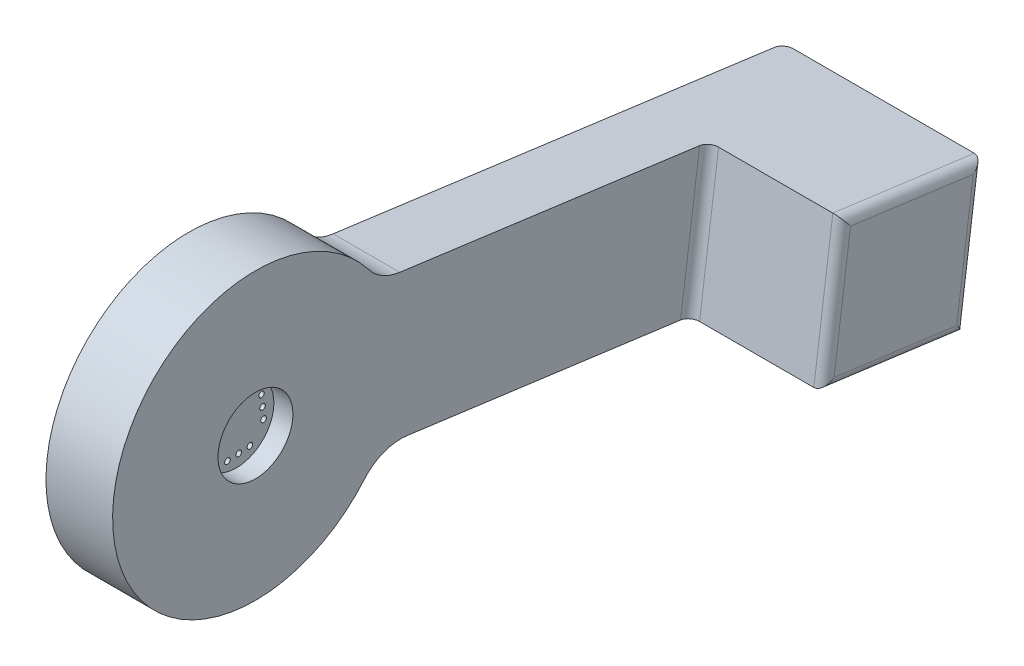
SolidWorks part; units mm, degrees
ref_plane "Front Plane" [suppressed] through (0, 0, 0) normal (0, 0, 1) x (1, 0, 0)
ref_plane "Top Plane" [suppressed] through (0, 0, 0) normal (0, 1, 0) x (1, 0, 0)
ref_plane "Right Plane" through (0, 0, 0) normal (1, 0, 0) x (0, 0, -1)
sketch "Sketch1" plane through (0, 0, 0) normal (1, 0, 0) x (0, 0, -1)
  line L4 (32.8966, -19.2204) -> (153.708, -35.4166)
  line L5 (153.708, -35.4166) -> (158.7705, 2.3455)
  line L6 (158.7705, 2.3455) -> (32.8966, 19.2204)
  arc A2 (32.8966, 19.2204) -> (32.8966, -19.2204) centre (0, 0) ccw
  dimension "D2" = 127
  dimension "D1" = 38.1
  dimension "D3" = 38.1
extrude "Boss-Extrude1" add sketch "Sketch1" along normal blind 17.78
sketch "Sketch2" plane through (17.78, 0, 0) normal (1, 0, 0) x (0, 0, -1)
  circle A0 centre (0, 0) radius 10
extrude "Cut-Extrude2" cut sketch "Sketch2" against normal blind 5.08
sketch "Sketch8" plane through (12.7, 0, 0) normal (1, 0, 0) x (0, 0, -1)
  circle A12 centre (-7.2367, 2.3729) radius 0.75
  circle A13 centre (-6.9729, -0.6155) radius 0.75
  circle A14 centre (-6.7091, -3.6039) radius 0.75
  circle A15 centre (-2.3729, -7.2367) radius 0.75
  circle A16 centre (0.6155, -6.9729) radius 0.75
  circle A17 centre (3.6039, -6.7091) radius 0.75
  circle A18 centre (7.2367, -2.3729) radius 0.75
  circle A19 centre (6.9729, 0.6155) radius 0.75
  circle A20 centre (6.7091, 3.6039) radius 0.7248
  circle A21 centre (2.3729, 7.2367) radius 0.75
  circle A22 centre (-0.6155, 6.9729) radius 0.75
  circle A23 centre (-3.6039, 6.7091) radius 0.7425
extrude "Cut-Extrude7" cut sketch "Sketch8" against normal blind 5.08
sketch "Sketch4" plane through (17.78, 0, 0) normal (1, 0, 0) x (0, 0, -1)
  line L0 (158.7705, 2.3455) -> (153.708, -35.4166)
  line L1 (158.7705, 2.3455) -> (121.0083, 7.408)
  line L2 (153.708, -35.4166) -> (115.9458, -30.3542)
  line L3 (121.0083, 7.408) -> (115.9458, -30.3542)
  line L4 (158.7705, 2.3455) -> (115.9458, -30.3542) construction
  line L5 (121.0083, 7.408) -> (153.708, -35.4166) construction
  line L6 (156.2392, -16.5355) -> (137.3582, -14.0043) construction
  dimension "D1" = 38.1
  dimension "D2" = 38.1
extrude "Boss-Extrude2" add sketch "Sketch4" along normal blind 35.56
sketch "Sketch7" plane through (0, -20.8679, -155.6585) normal (0, -0.1329, -0.9911) x (-1, 0, 0)
  line L0 (-53.34, 4.3711) -> (0, 4.3711) construction
  line L1 (-47.3438, -5.6619) -> (-6.1958, -5.6619)
  line L2 (-47.3438, -5.6619) -> (-47.3438, 14.4041)
  line L3 (-47.3438, 14.4041) -> (-6.1958, 14.4041)
  line L4 (-6.1958, -5.6619) -> (-6.1958, 14.4041)
  line L5 (-47.3438, -5.6619) -> (-6.1958, 14.4041) construction
  line L6 (-47.3438, 14.4041) -> (-6.1958, -5.6619) construction
  line L7 (-53.34, -14.6789) -> (-53.34, 23.4211) construction
  line L8 (0, -14.6789) -> (0, 23.4211) construction
  point P0 (-26.7698, 4.3711)
  dimension "D1" = 41.148
  dimension "D2" = 20.066
extrude "Cut-Extrude5" cut sketch "Sketch7" against normal blind 26.797
fillet "Fillet2" radius 2.54 1 edges at (17.78, -11.4731, -118.4771)
fillet "Fillet3" radius 2.54 4 edges at (53.34, -16.5355, -156.2392) (53.34, -32.8854, -134.8269) (53.34, -11.4731, -118.4771) (53.34, 4.8768, -139.8894)
fillet "Fillet4" radius 2.54 1 edges at (0, -16.5355, -156.2392)
fillet "Fillet5" radius 12.7 2 edges at (8.89, -19.2204, -32.8966) (8.89, 19.2204, -32.8966)
